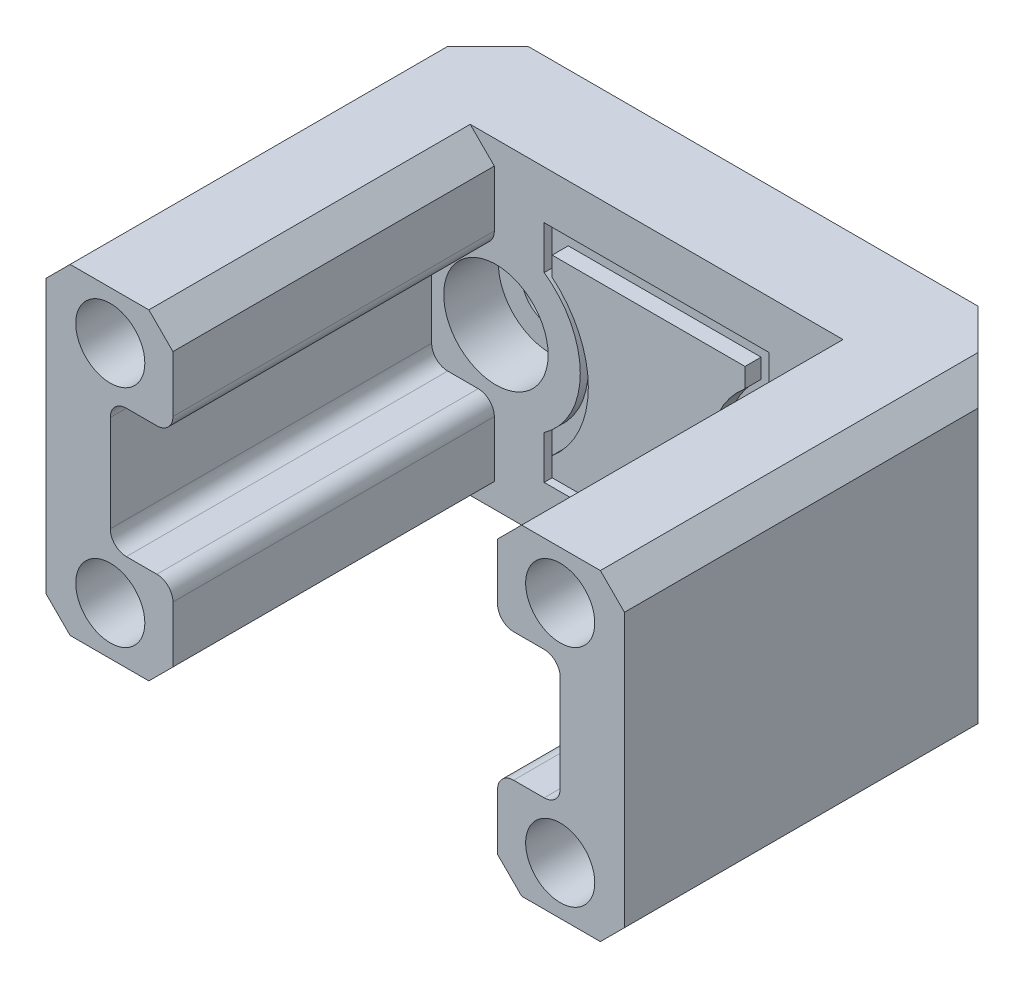
SolidWorks part; units mm, degrees
material "PETG"
ref_plane "Płaszczyzna przednia" through (0, 0, 0) normal (0, 0, 1) x (1, 0, 0)
ref_plane "Płaszczyzna górna" through (0, 0, 0) normal (0, 1, 0) x (1, 0, 0)
ref_plane "Płaszczyzna prawa" through (0, 0, 0) normal (1, 0, 0) x (0, 0, -1)
sketch "Sketch1" plane through (0, 0, 0) normal (0, 0, 1) x (1, 0, 0)
  line L1 (0, 0) -> (28, 0)
  line L2 (0, 0) -> (0, 20)
  line L3 (0, 20) -> (28, 20)
  line L4 (28, 0) -> (28, 20)
  dimension "D1" = 20
  dimension "D2" = 28
extrude "Boss-Extrude1" add sketch "Sketch1" along normal blind 6
hole_wizard "CBORE for M3 Hex Socket Head Cap Screw1" positions "Sketch2" profile "Sketch4" counterbore size "M3" standard "DIN" end condition through all
sketch "Sketch2" plane through (0, 0, 6) normal (0, 0, 1) x (1, 0, 0)
  line L1 (0, 10) -> (4, 10) construction
  line L2 (0, 20) -> (0, 0) construction
  line L3 (4, 10) -> (24, 10) construction
  line L5 (28, 10) -> (24, 10) construction
  line L6 (28, 0) -> (28, 20) construction
  point P0 (4, 10)
  point P2 (24, 10)
  dimension "D1" = 20
sketch "Sketch4" plane through (4, 10, 6) normal (1, 0, 0) x (0, -1, 0)
  line L0 (0, 0) -> (0, 6)
  line L1 (0, 6) -> (1.8, 6)
  line L3 (1.8, 6) -> (1.8, 3.4)
  line L4 (1.8, 3.4) -> (3.25, 3.4)
  line L5 (3.25, 3.4) -> (3.25, 0)
  line L7 (3.25, 0) -> (0, 0)
  line L11 (0, -6.35) -> (0, 107.95) construction
  dimension "Thru Hole Dia." = 3.6
  dimension "Thru Hole Depth" = 6
  dimension "C'Bore Dia." = 6.5
  dimension "C'Bore Depth" = 3.4
sketch "Sketch5" plane through (0, 0, 6) normal (0, 0, 1) x (1, 0, 0)
  line L0 (24.1, 20) -> (24.1, 14)
  line L1 (0, 20) -> (3.9, 20)
  line L2 (0, 20) -> (0, 14)
  line L3 (0, 14) -> (3.9, 14)
  line L4 (3.9, 20) -> (3.9, 14)
  line L9 (24.1, 20) -> (28, 20)
  line L10 (28, 20) -> (28, 14)
  line L11 (24.1, 14) -> (28, 14)
  line L12 (24.1, 6) -> (24.1, 0)
  line L13 (24.1, 6) -> (28, 6)
  line L14 (28, 6) -> (28, 0)
  line L15 (24.1, 0) -> (28, 0)
  line L16 (0, 6) -> (0, 0)
  line L17 (0, 6) -> (3.9, 6)
  line L18 (3.9, 6) -> (3.9, 0)
  line L19 (0, 0) -> (3.9, 0)
  line L20 (28, 0) -> (28, 20) construction
  line L21 (0, 0) -> (28, 0) construction
  dimension "D1" = 20.2
  dimension "D2" = 6
  dimension "D3" = 2
  dimension "D4" = 2
extrude "Boss-Extrude2" add sketch "Sketch5" along normal blind 20
sketch "Sketch6" plane through (0, 0, 0) normal (0, 0, -1) x (-1, 0, 0)
  line L0 (-28, 20) -> (0, 20) construction
  line L1 (-28, 20) -> (-32, 20)
  line L2 (-28, 20) -> (-28, 0)
  line L3 (-28, 0) -> (-32, 0)
  line L4 (-32, 20) -> (-32, 0)
  line L5 (0, 0) -> (4, 0)
  line L6 (0, 0) -> (0, 20)
  line L7 (0, 20) -> (4, 20)
  line L8 (4, 0) -> (4, 20)
  line L9 (0, 0) -> (-28, 0) construction
  dimension "D1" = 4
extrude "Boss-Extrude3" add sketch "Sketch6" against normal up to surface (26 mm away) up to face at (26.05, 17, 26)
fillet "Fillet1" radius 1 8 edges at (0, 14, 16) (0, 6, 16) (28, 14, 16) (28, 6, 16) (3.9, 14, 16) (3.9, 6, 16) (24.1, 14, 16) (24.1, 6, 16)
hole_wizard "Ø4.3 (4.3) Diameter Hole1" positions "Sketch7" profile "Sketch8" hole size "Ø4.3" standard "DIN"
sketch "Sketch7" plane through (0, 0, 26) normal (0, 0, 1) x (1, 0, 0)
  line L1 (-4, 20) -> (0, 20) construction
  line L2 (-4, 20) -> (-4, 17) construction
  line L3 (-4, 17) -> (0, 17) construction
  line L4 (0, 20) -> (0, 17) construction
  line L5 (14, 20) -> (14, 2.3578)
  line L6 (24.1, 20) -> (3.9, 20) construction
  line L8 (-4, 10) -> (16.4891, 10)
  line L9 (-4, 20) -> (-4, 0) construction
  point P1 (0, 17)
  point P60 (0, 3)
  point P62 (28, 3)
  point P63 (28, 17)
  dimension "D1" = 3
  dimension "D2" = 4
sketch "Sketch8" plane through (28, 17, 26) normal (1, 0, 0) x (0, -1, 0)
  line L0 (0, 0) -> (0, 11.2919)
  line L1 (0, 11.2919) -> (2.15, 10)
  line L2 (2.15, 10) -> (2.15, 0)
  line L5 (2.15, 0) -> (0, 0)
  line L10 (0, 11.2919) -> (-2.15, 10) construction
  line L11 (0, -6.35) -> (0, 107.95) construction
  dimension "Hole Dia." = 4.3
  dimension "Hole Depth" = 10
  dimension "Drill Angle" = 118
chamfer "Chamfer1" distance 1.5 angle 45 8 edges at (24.1, 20, 16) (24.1, 0, 16) (3.9, 20, 16) (3.9, 0, 16) (-4, 0, 13) (-4, 20, 13) (32, 0, 13) (32, 20, 13)
sketch "Sketch9" plane through (0, 0, 6) normal (0, 0, 1) x (1, 0, 0)
  line L0 (14, 17) -> (14, 20) construction
  line L1 (7, 17) -> (21, 17)
  line L2 (7, 17) -> (7, 3)
  line L3 (7, 3) -> (21, 3)
  line L4 (21, 17) -> (21, 3)
  line L5 (25.6, 20) -> (2.4, 20) construction
  line L6 (7, 10) -> (-4, 10) construction
  line L7 (-4, 18.5) -> (-4, 1.5) construction
  circle A0 centre (24, 10) radius 3.25 construction
  circle A1 centre (4, 10) radius 3.25 construction
  circle A2 centre (24, 10) radius 3.25
  circle A3 centre (4, 10) radius 3.25
  circle A4 centre (4, 10) radius 5.25
  circle A5 centre (24, 10) radius 5.25
  dimension "D2" = 14
  dimension "D3" = 14
  dimension "D1" = 2
extrude "Cut-Extrude1" cut sketch "Sketch9" against normal blind 0.5 contours A5 L4 L1 L2 A4 L3
sketch "Sketch10" plane through (0, 0, 5.5) normal (0, 0, 1) x (1, 0, 0)
  line L0 (20, 4) -> (20, 5.1977)
  line L1 (8, 4) -> (20, 4)
  line L2 (8, 5.1977) -> (8, 4)
  line L3 (8, 16) -> (8, 14.8023)
  line L4 (20, 16) -> (8, 16)
  line L5 (20, 14.8023) -> (20, 16)
  line L6 (21, 14.3084) -> (21, 17)
  line L7 (21, 17) -> (7, 17)
  line L8 (7, 17) -> (7, 14.3084)
  line L9 (7, 5.6916) -> (7, 3)
  line L10 (7, 3) -> (21, 3)
  line L11 (21, 3) -> (21, 5.6916)
  line L12 (21, 14.3084) -> (21, 17)
  line L13 (21, 17) -> (7, 17)
  line L14 (7, 17) -> (7, 14.3084)
  line L15 (7, 5.6916) -> (7, 3)
  line L16 (7, 3) -> (21, 3)
  line L17 (21, 3) -> (21, 5.6916)
  arc A0 (20, 14.8023) -> (20, 5.1977) centre (24, 10) ccw
  arc A1 (8, 5.1977) -> (8, 14.8023) centre (4, 10) ccw
  arc A2 (21, 14.3084) -> (21, 5.6916) centre (24, 10) ccw
  arc A3 (7, 5.6916) -> (7, 14.3084) centre (4, 10) ccw
  arc A4 (21, 14.3084) -> (21, 5.6916) centre (24, 10) ccw
  arc A5 (7, 5.6916) -> (7, 14.3084) centre (4, 10) ccw
  dimension "D1" = 0
  dimension "D2" = 1
extrude "Boss-Extrude4" add sketch "Sketch10" along normal blind 1 separate body contours A1 L2 L1 L0 A0 L5 L4 L3
chamfer "Chamfer3" distance 4 angle 45 2 edges at (-4, 10, 0) (32, 10, 0)
